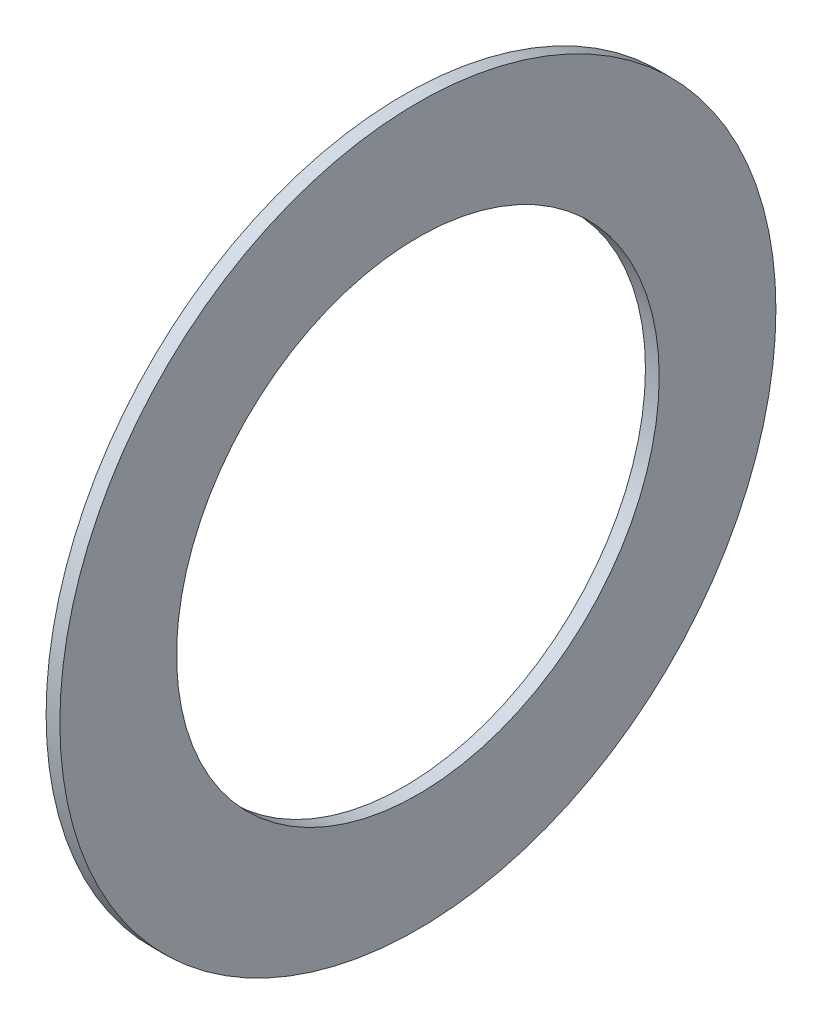
SolidWorks part; units mm, degrees
ref_plane "Front Plane" through (0, 0, 0) normal (0, 0, 1) x (1, 0, 0)
ref_plane "Top Plane" through (0, 0, 0) normal (0, 1, 0) x (1, 0, 0)
ref_plane "Right Plane" through (0, 0, 0) normal (1, 0, 0) x (0, 0, -1)
sketch "Sketch1" plane through (0, 0, 0) normal (1, 0, 0) x (0, 0, -1)
  circle A0 centre (0, 0) radius 26
  circle A1 centre (0, 0) radius 17.5 construction
  circle A2 centre (0, 0) radius 17.525
  dimension "OD" = 52
  dimension "For Shaft Diameter" = 35
  dimension "ID" = 35.05
sketch "Sketch2" plane through (0, 0, 0) normal (0, 0, 1) x (1, 0, 0)
  line L0 (0.5, 0) -> (-0.5, 0) construction
  line L1 (0.5, -26) -> (-0.5, -26) construction
  line L2 (0.5, -26) -> (0.5, 26) construction
  line L3 (0.5, 26) -> (-0.5, 26) construction
  line L4 (-0.5, -26) -> (-0.5, 26) construction
  point P6 (0, 26)
  point P9 (0, -26)
  dimension "Thickness" = 1
sketch "Sketch3" plane through (0, 0, 0) normal (1, 0, 0) x (0, 0, -1)
  circle A1 centre (0, 0) radius 26 construction
  circle A3 centre (0, 0) radius 26
  circle A4 centre (0, 0) radius 17.525 construction
  circle A5 centre (0, 0) radius 17.525
extrude "Boss-Extrude1" add sketch "Sketch3" along normal up to vertex (0.5 mm away) and the other way up to vertex (0.5 mm away) up to point (0.5, 26, 0) other way up to point (-0.5, 26, 0)
